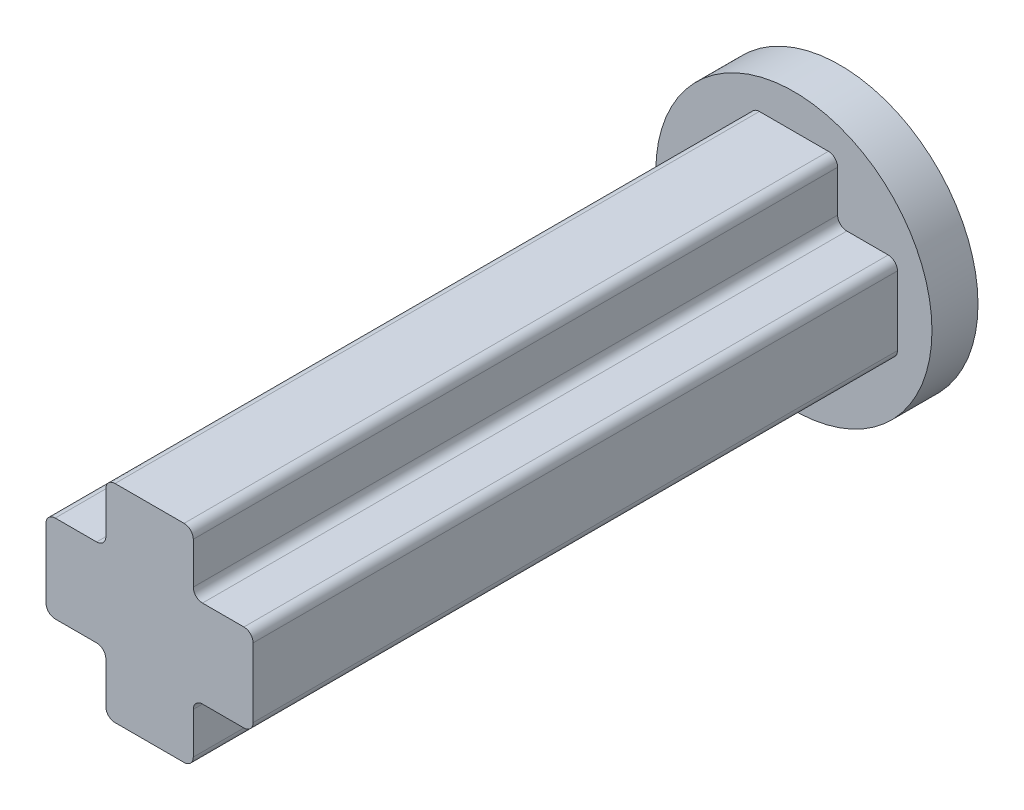
SolidWorks part; units mm, degrees
ref_plane "Front Plane" through (0, 0, 0) normal (1, 0, 0) x (0, 1, 0)
ref_plane "Top Plane" through (0, 0, 0) normal (0, 0, 1) x (0, 1, 0)
ref_plane "Right Plane" through (0, 0, 0) normal (0, 1, 0) x (-1, 0, 0)
sketch "Sketch1" plane through (0, 0, 0) normal (0, 0, 1) x (0, 1, 0)
  circle A0 centre (0, 0) radius 3
extrude "Boss-Extrude1" add sketch "Sketch1" along normal blind 1
sketch "Sketch2" plane through (0, 0, 1) normal (0, 0, 1) x (1, 0, 0)
  line L4 (-0.95, 2.05) -> (-0.95, 1.15)
  line L5 (-1.15, 0.95) -> (-2.05, 0.95)
  line L7 (2.05, -0.95) -> (1.15, -0.95)
  line L12 (0.95, -1.15) -> (0.95, -2.05)
  line L13 (-2.05, -0.95) -> (-1.15, -0.95)
  line L14 (-0.95, -1.15) -> (-0.95, -2.05)
  line L17 (0.95, 2.05) -> (0.95, 1.15)
  line L18 (1.15, 0.95) -> (2.05, 0.95)
  line L20 (-2.25, -0.75) -> (-2.25, 0.75)
  line L21 (-0.75, 2.25) -> (0.75, 2.25)
  line L22 (2.25, 0.75) -> (2.25, -0.75)
  line L23 (0.75, -2.25) -> (-0.75, -2.25)
  arc A0 (-2.25, 0.75) -> (-2.05, 0.95) centre (-2.05, 0.75) cw
  arc A1 (-2.25, -0.75) -> (-2.05, -0.95) centre (-2.05, -0.75) ccw
  arc A2 (-0.95, -2.05) -> (-0.75, -2.25) centre (-0.75, -2.05) ccw
  arc A3 (0.75, -2.25) -> (0.95, -2.05) centre (0.75, -2.05) ccw
  arc A4 (2.05, -0.95) -> (2.25, -0.75) centre (2.05, -0.75) ccw
  arc A5 (2.05, 0.95) -> (2.25, 0.75) centre (2.05, 0.75) cw
  arc A6 (0.75, 2.25) -> (0.95, 2.05) centre (0.75, 2.05) cw
  arc A7 (-0.95, 2.05) -> (-0.75, 2.25) centre (-0.75, 2.05) cw
  arc A8 (1.15, -0.95) -> (0.95, -1.15) centre (1.15, -1.15) ccw
  arc A9 (0.95, 1.15) -> (1.15, 0.95) centre (1.15, 1.15) ccw
  arc A10 (-0.95, 1.15) -> (-1.15, 0.95) centre (-1.15, 1.15) cw
  arc A11 (-1.15, -0.95) -> (-0.95, -1.15) centre (-1.15, -1.15) cw
  dimension "D1" = 0.2
  dimension "D2" = 0.2
extrude "Boss-Extrude2" add sketch "Sketch2" along normal blind 14 contours L7 A8 L12 A3 L23 A2 L14 A11 L13 A1 L20 A0 L5 A10 L4 A7 L21 A6 L17 A9 L18 A5 L22 A4
